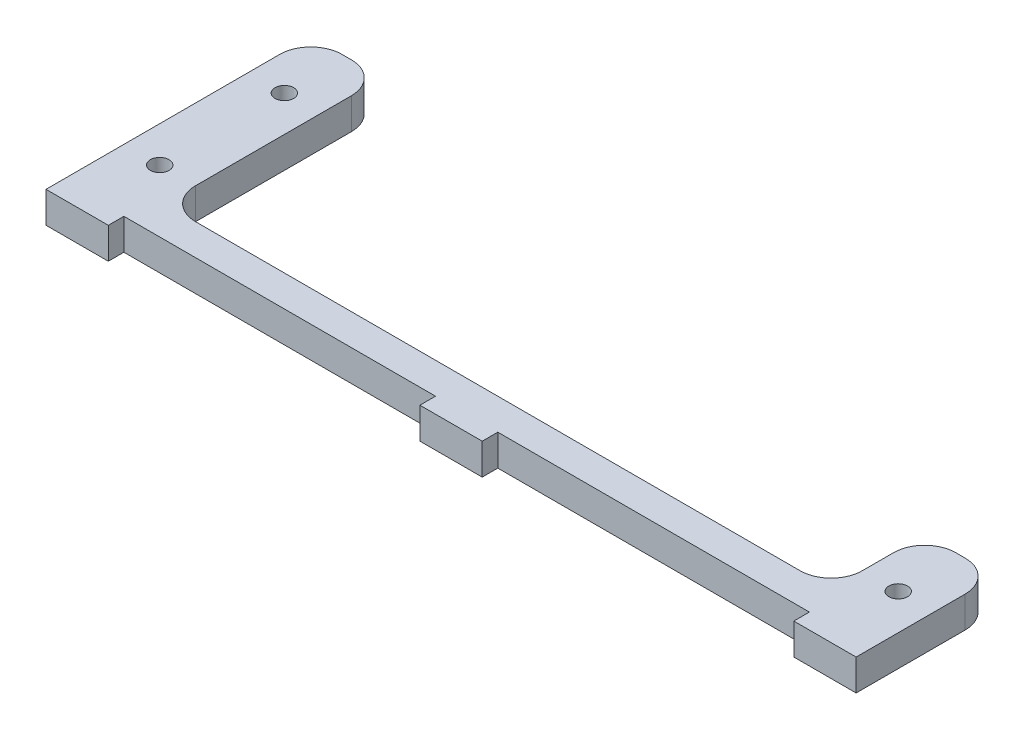
SolidWorks part; units mm, degrees
ref_plane "Front Plane" through (0, 0, 0) normal (0, 0, 1) x (1, 0, 0)
ref_plane "Top Plane" through (0, 0, 0) normal (0, 1, 0) x (1, 0, 0)
ref_plane "Right Plane" through (0, 0, 0) normal (1, 0, 0) x (0, 0, -1)
sketch "Sketch1" plane through (0, 0, 0) normal (0, 1, 0) x (1, 0, 0)
  line L0 (88.9, -6.35) -> (152.4, -6.35)
  line L1 (20.955, 0) -> (144.145, 0)
  line L2 (0, 0) -> (0, -6.35)
  line L3 (12.7, -6.35) -> (76.2, -6.35)
  line L4 (165.1, 0) -> (165.1, -6.35)
  line L6 (0, -6.35) -> (0, -9.525)
  line L7 (0, -9.525) -> (12.7, -9.525)
  line L8 (12.7, -6.35) -> (12.7, -9.525)
  line L10 (165.1, -6.35) -> (165.1, -9.525)
  line L11 (165.1, -9.525) -> (152.4, -9.525)
  line L12 (152.4, -6.35) -> (152.4, -9.525)
  line L14 (76.2, -6.35) -> (76.2, -9.525)
  line L15 (76.2, -9.525) -> (88.9, -9.525)
  line L16 (88.9, -6.35) -> (88.9, -9.525)
  line L18 (0, 0) -> (0, 38.1)
  line L19 (6.35, 44.45) -> (8.255, 44.45)
  line L20 (14.605, 6.35) -> (14.605, 38.1)
  line L22 (165.1, 0) -> (165.1, 12.7)
  line L23 (158.75, 19.05) -> (156.845, 19.05)
  line L24 (150.495, 6.35) -> (150.495, 12.7)
  circle A0 centre (7.3025, 31.75) radius 1.905
  circle A1 centre (7.3025, 6.35) radius 1.905
  circle A2 centre (157.7975, 6.3531) radius 1.905
  arc A3 (156.845, 19.05) -> (150.495, 12.7) centre (156.845, 12.7) ccw
  arc A4 (165.1, 12.7) -> (158.75, 19.05) centre (158.75, 12.7) ccw
  arc A5 (8.255, 44.45) -> (14.605, 38.1) centre (8.255, 38.1) cw
  arc A6 (0, 38.1) -> (6.35, 44.45) centre (6.35, 38.1) cw
  arc A7 (144.145, 0) -> (150.495, 6.35) centre (144.145, 6.35) ccw
  arc A8 (20.955, 0) -> (14.605, 6.35) centre (20.955, 6.35) cw
  point P29 (150.495, 19.05)
  point P32 (165.1, 19.05)
  point P35 (14.605, 44.45)
  point P38 (0, 44.45)
  dimension "D10" = 3.81
  dimension "D21" = 6.35
  dimension "D22" = 6.35
  dimension "D1" = 6.35
  dimension "D2" = 165.1
  dimension "D3" = 3.175
  dimension "D4" = 12.7
  dimension "D5" = 12.7
  dimension "D6" = 3.175
  dimension "D7" = 3.175
  dimension "D8" = 12.7
  dimension "D9" = 63.5
  dimension "D11" = 25.4
  dimension "D12" = 150.495
  dimension "D13" = 25.3969
  dimension "D14" = 12.7
  dimension "D15" = 7.3025
  dimension "D16" = 152.6229
  dimension "D17" = 14.605
  dimension "D18" = 44.45
  dimension "D19" = 14.605
  dimension "D20" = 19.05
extrude "Boss-Extrude1" add sketch "Sketch1" along normal blind 6.35
